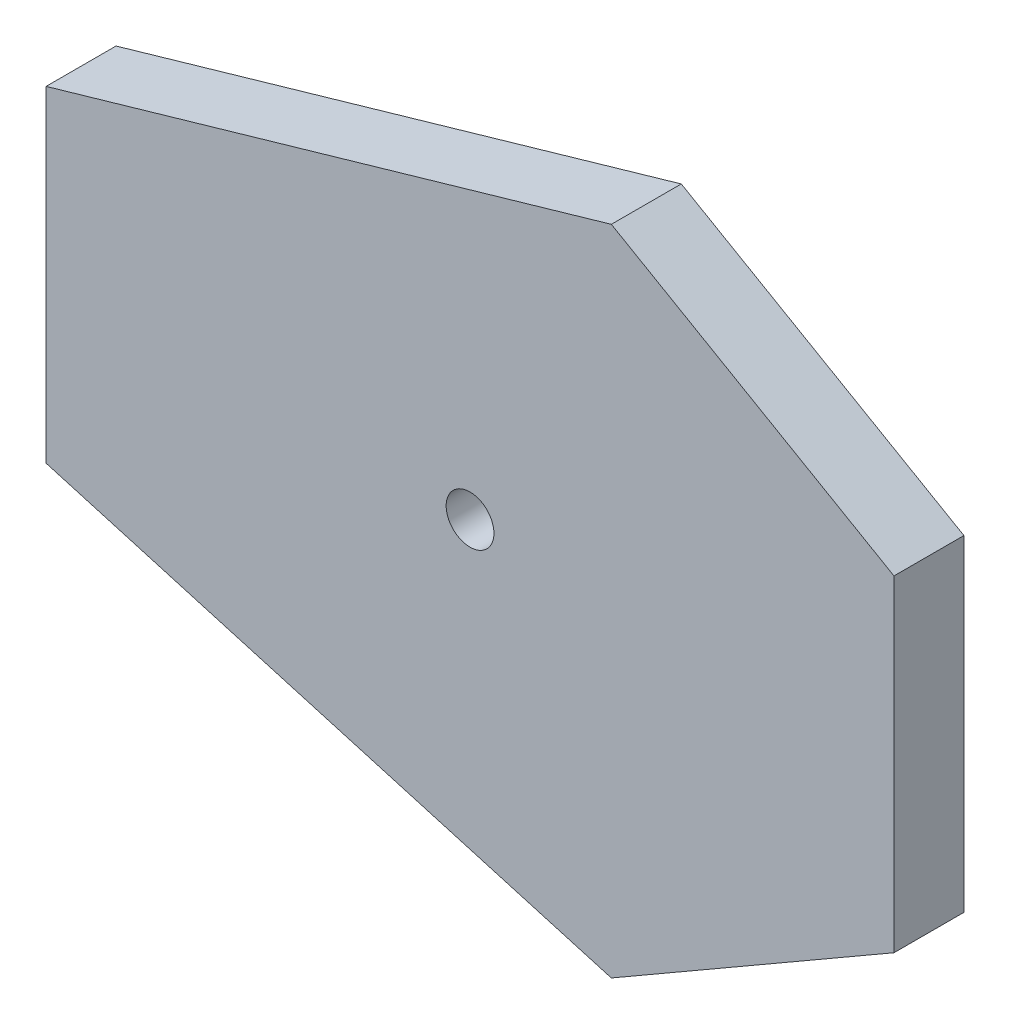
SolidWorks part; units mm, degrees
ref_plane "Front Plane" through (0, 0, 0) normal (0, 0, 1) x (1, 0, 0)
ref_plane "Top Plane" through (0, 0, 0) normal (0, 1, 0) x (1, 0, 0)
ref_plane "Right Plane" through (0, 0, 0) normal (1, 0, 0) x (0, 0, -1)
sketch "Sketch1" plane through (0, 0, 0) normal (0, 0, 1) x (1, 0, 0)
  line L0 (-41.5231, 14) -> (-41.5231, -14) construction
  line L1 (6.9744, -28) -> (-41.5231, -14) construction
  line L2 (6.9744, -28) -> (31.2231, -14) construction
  line L3 (31.2231, -14) -> (31.2231, 14) construction
  line L4 (31.2231, 14) -> (6.9744, 28) construction
  line L5 (-41.5231, 14) -> (6.9744, 28) construction
  line L6 (-41.5231, 14) -> (-41.5231, -14)
  line L7 (6.9744, -28) -> (-41.5231, -14)
  line L8 (6.9744, -28) -> (31.2231, -14)
  line L9 (31.2231, -14) -> (31.2231, 14)
  line L10 (31.2231, 14) -> (6.9744, 28)
  line L11 (-41.5231, 14) -> (6.9744, 28)
  circle A0 centre (-5.15, 0) radius 2.05
  dimension "D1" = 4.1
extrude "Boss-Extrude1" add sketch "Sketch1" along normal blind 6
sketch "Sketch2" plane through (0, 0, 0) normal (0, 0, -1) x (-1, 0, 0)
  arc A1 (5.8221, -1.9895) -> (5.8221, 1.9895) centre (5.15, 0) ccw construction
  circle A2 centre (5.15, 0) radius 2.1
extrude "Cut-Extrude1" cut sketch "Sketch2" against normal blind 3
